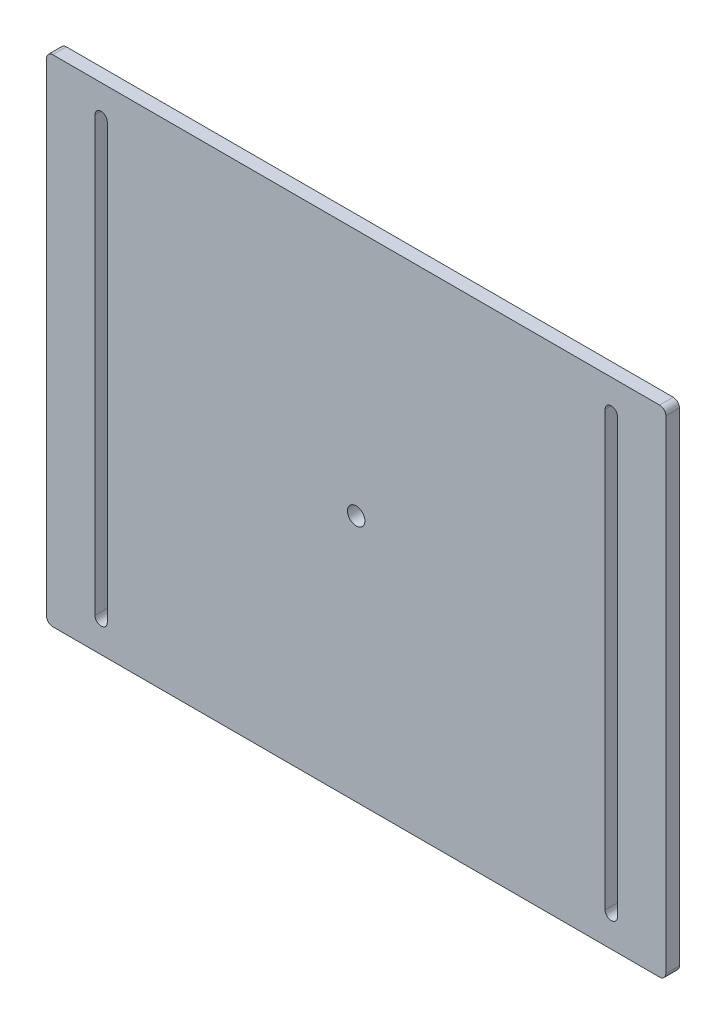
SolidWorks part; units mm, degrees
ref_plane "Front Plane" through (0, 0, 0) normal (0, 0, 1) x (1, 0, 0)
ref_plane "Top Plane" through (0, 0, 0) normal (0, 1, 0) x (1, 0, 0)
ref_plane "Right Plane" through (0, 0, 0) normal (1, 0, 0) x (0, 0, -1)
sketch "Sketch1" plane through (0, 0, 0) normal (0, 0, 1) x (1, 0, 0)
  line L0 (-104.6196, 88.9) -> (-104.6196, -88.9) construction
  line L1 (-127, -101.6) -> (127, -101.6)
  line L2 (-127, -101.6) -> (-127, 101.6)
  line L3 (-127, 101.6) -> (127, 101.6)
  line L4 (127, -101.6) -> (127, 101.6)
  line L5 (-127, -101.6) -> (127, 101.6) construction
  line L6 (-127, 101.6) -> (127, -101.6) construction
  line L7 (-102.0923, 88.9) -> (-102.0923, -88.9)
  line L8 (-107.1469, 88.9) -> (-107.1469, -88.9)
  line L9 (104.6196, 88.9) -> (104.6196, -88.9) construction
  line L10 (107.1469, 88.9) -> (107.1469, -88.9)
  line L11 (102.0923, 88.9) -> (102.0923, -88.9)
  line L12 (-104.6196, 0) -> (-127, 0) construction
  line L13 (104.6196, 0) -> (127, 0) construction
  arc A0 (-102.0923, 88.9) -> (-107.1469, 88.9) centre (-104.6196, 88.9) ccw
  arc A1 (-107.1469, -88.9) -> (-102.0923, -88.9) centre (-104.6196, -88.9) ccw
  arc A2 (107.1469, 88.9) -> (102.0923, 88.9) centre (104.6196, 88.9) ccw
  arc A3 (102.0923, -88.9) -> (107.1469, -88.9) centre (104.6196, -88.9) ccw
  point P0 (0, 0)
  point P8 (-104.6196, 0)
  point P13 (104.6196, 0)
  dimension "D4" = 2.5273
  dimension "D1" = 254
  dimension "D2" = 203.2
  dimension "D3" = 209.2391
  dimension "D5" = 12.7
extrude "Boss-Extrude1" add sketch "Sketch1" along normal blind 5.588
hole_wizard "1/4 Clearance Hole1" positions "Sketch3" profile "Sketch2" hole size "1/4" standard "ANSI Inch" end condition through all
sketch "Sketch3" plane through (0, 0, 5.588) normal (0, 0, 1) x (1, 0, 0)
  point P0 (0, 0)
sketch "Sketch2" plane through (0, 0, 5.588) normal (1, 0, 0) x (0, -1, 0)
  line L0 (0, 0) -> (0, 5.588)
  line L1 (0, 5.588) -> (3.5712, 5.588)
  line L2 (3.5712, 5.588) -> (3.5712, 0)
  line L5 (3.5712, 0) -> (0, 0)
  line L11 (0, -6.35) -> (0, 107.95) construction
  dimension "Thru Hole Dia." = 7.1425
  dimension "Thru Hole Depth" = 5.588
fillet "Fillet1" radius 2.54 4 edges at (-127, -101.6, 2.794) (127, -101.6, 2.794) (127, 101.6, 2.794) (-127, 101.6, 2.794)
